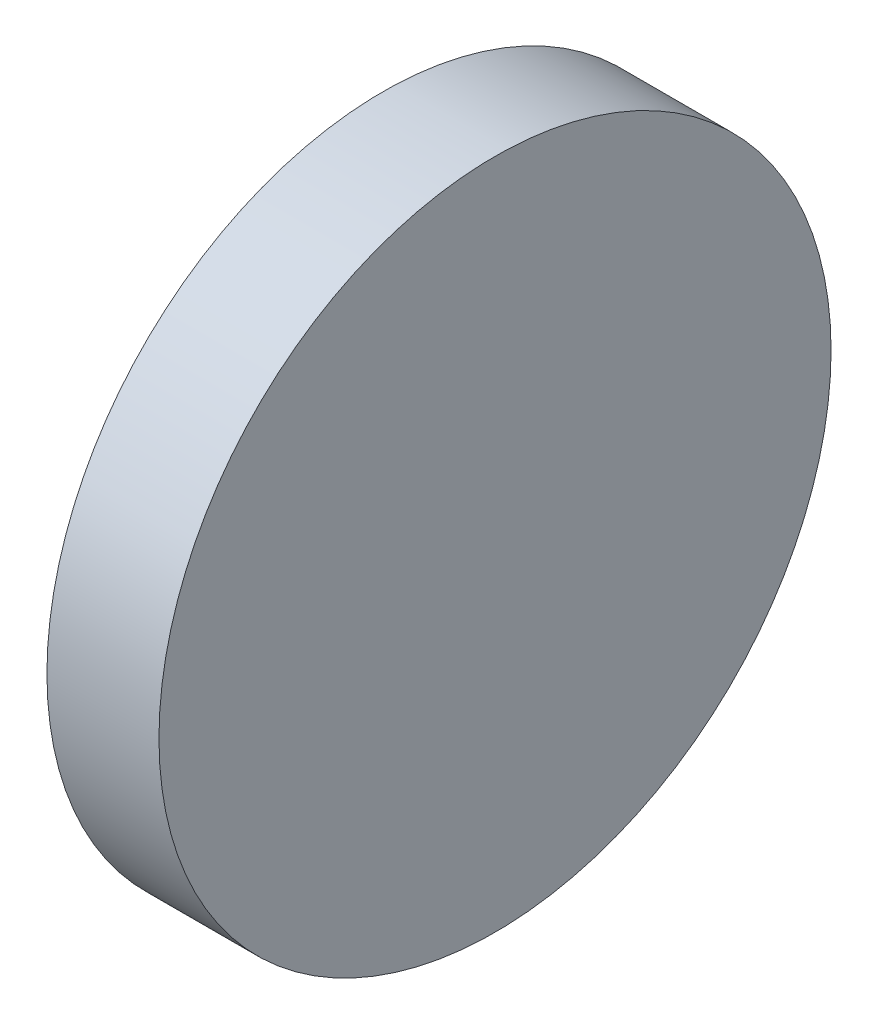
SolidWorks part; units mm, degrees
ref_plane "Front Plane" through (0, 0, 0) normal (0, 0, 1) x (1, 0, 0)
ref_plane "Top Plane" through (0, 0, 0) normal (0, 1, 0) x (1, 0, 0)
ref_plane "Right Plane" through (0, 0, 0) normal (1, 0, 0) x (0, 0, -1)
sketch "Sketch1" plane through (0, 0, 0) normal (0, 0, 1) x (1, 0, 0)
  line L0 (-163.1016, 0) -> (7991.9803, 0) construction
  line L1 (0, 0) -> (0, 3)
  line L2 (0, 3) -> (1, 3)
  line L3 (1, 3) -> (1, 0)
  line L4 (1, 0) -> (0, 0)
  dimension "D1" = 6
  dimension "D2" = 1
revolve "Revolve1" add sketch "Sketch1" angle 360 about L0
